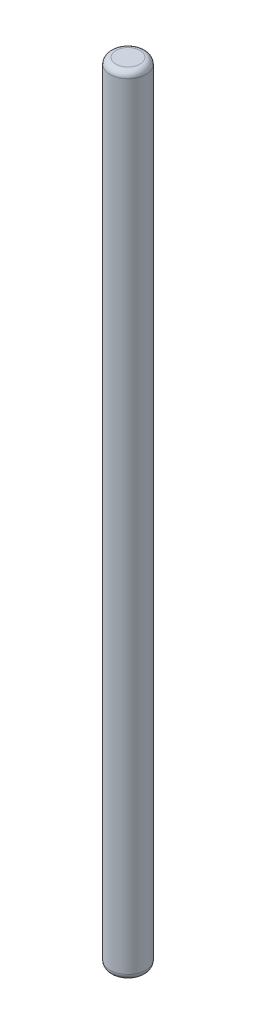
SolidWorks part; units mm, degrees
ref_plane "Front Plane" through (0, 0, 0) normal (0, 0, 1) x (1, 0, 0)
ref_plane "Top Plane" through (0, 0, 0) normal (0, 1, 0) x (1, 0, 0)
ref_plane "Right Plane" through (0, 0, 0) normal (1, 0, 0) x (0, 0, -1)
sketch "Sketch1" plane through (0, 0, 0) normal (0, 1, 0) x (1, 0, 0)
  circle A0 centre (0, 0) radius 3
  dimension "D1" = 6
extrude "Boss-Extrude1" add sketch "Sketch1" along normal blind 132
fillet "Fillet1" radius 1 2 edges at (0, 0, 3) (0, 132, 3)
